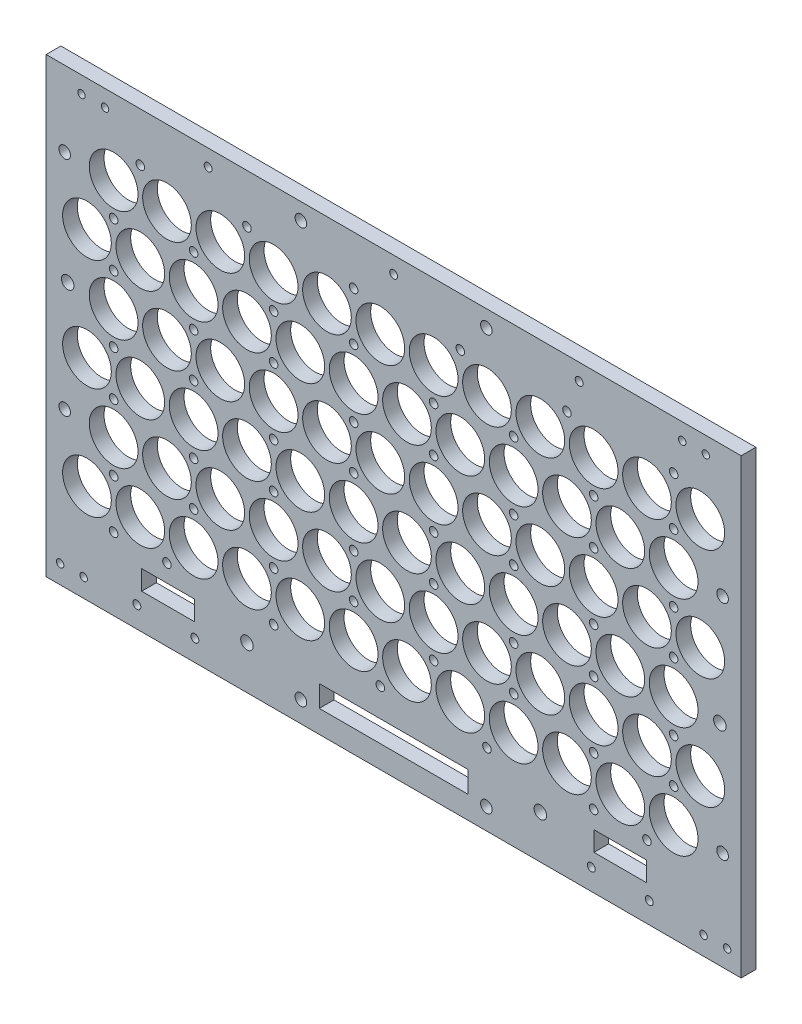
SolidWorks part; units mm, degrees
material "ABS"
ref_plane "X-Y Datum" through (0, 0, 0) normal (0, 0, 1) x (1, 0, 0)
ref_plane "X-Z Datum" through (0, 0, 0) normal (0, 1, 0) x (1, 0, 0)
ref_plane "Y-Z Datum" through (0, 0, 0) normal (1, 0, 0) x (0, 0, -1)
sketch "Sketch1" plane through (0, 0, 0) normal (0, 0, 1) x (1, 0, 0)
  line L1 (-143.025, 70.775) -> (143.025, 70.775)
  line L2 (-143.025, 70.775) -> (-143.025, -70.775)
  line L3 (-143.025, -70.775) -> (143.025, -70.775)
  line L4 (143.025, 70.775) -> (143.025, -70.775)
  line L5 (-143.025, 70.775) -> (143.025, -70.775) construction
  line L6 (-143.025, -70.775) -> (143.025, 70.775) construction
  line L13 (-149.85, -102.6) -> (149.85, -102.6)
  line L14 (-149.85, 91.65) -> (149.85, 91.65)
  line L15 (-149.85, 91.65) -> (-149.85, -102.6)
  line L16 (149.85, 91.65) -> (149.85, -102.6)
  line L17 (149.85, 70.775) -> (149.85, -70.775) construction
  line L18 (-143.025, 91.65) -> (143.025, 91.65) construction
  line L19 (-143.025, -102.6) -> (143.025, -102.6) construction
  line L20 (-149.85, 70.775) -> (-149.85, -70.775) construction
  line L21 (-132.25, -60) -> (-109.25, -60) construction
  circle A0 centre (-132.25, -60) radius 10.775
  circle A1 centre (-109.25, -60) radius 10.775 construction
  circle A2 centre (-120.75, -36) radius 10.775
  point P0 (0, 0)
  point P16 (-120.75, -60)
  dimension "D1" = 21.55
  dimension "D2" = 23
  dimension "D3" = 24
  dimension "D5" = 141.55
  dimension "D6" = 286.05
  dimension "D7" = 31.825
  dimension "D8" = 20.875
  dimension "D9" = 6.825
  dimension "D10" = 6.825
extrude "Boss-Extrude1" add sketch "Sketch1" along normal blind 6.35
sketch "Sketch3" plane through (0, 0, 6.35) normal (0, 0, 1) x (1, 0, 0)
  line L4 (143.025, 70.775) -> (-143.025, 70.775)
  line L5 (143.025, -70.775) -> (143.025, 70.775)
  line L6 (-143.025, -70.775) -> (143.025, -70.775)
  line L7 (-143.025, 70.775) -> (-143.025, -70.775)
  line L8 (143.025, 70.775) -> (-143.025, 70.775)
  line L9 (143.025, -70.775) -> (143.025, 70.775)
  line L10 (-143.025, -70.775) -> (143.025, -70.775)
  line L11 (-143.025, 70.775) -> (-143.025, -70.775)
  circle A0 centre (-132.25, -60) radius 10.4988
  circle A1 centre (-120.75, -36) radius 10.775
  circle A2 centre (-120.75, -36) radius 10.775 construction
  circle A3 centre (-132.25, -60) radius 10.775
  circle A4 centre (-132.25, -60) radius 10.775 construction
  circle A5 centre (-120.75, -36) radius 10.4988
  dimension "D4" = 20.9976
  dimension "D1" = 0
  dimension "D2" = 0
  dimension "D3" = 0
extrude "Cut-Extrude1" cut sketch "Sketch3" against normal through all contours A4 | A0
sketch "Sketch4" plane through (0, 0, 6.35) normal (0, 0, 1) x (1, 0, 0)
  line L12 (143.025, 70.775) -> (-143.025, 70.775)
  line L13 (-143.025, 70.775) -> (-143.025, -70.775)
  line L14 (-143.025, -70.775) -> (143.025, -70.775)
  line L15 (143.025, -70.775) -> (143.025, 70.775)
  line L16 (143.025, 70.775) -> (-143.025, 70.775)
  line L17 (-143.025, 70.775) -> (-143.025, -70.775)
  line L18 (-143.025, -70.775) -> (143.025, -70.775)
  line L19 (143.025, -70.775) -> (143.025, 70.775)
  circle A1 centre (-120.75, -36) radius 10.4988
  circle A3 centre (-120.75, -36) radius 10.4988
  circle A5 centre (-132.25, -60) radius 10.4988
  circle A6 centre (-132.25, -60) radius 10.4988
  dimension "D1" = 0
  dimension "D2" = 0
  dimension "D3" = 0
extrude "Cut-Extrude2" cut sketch "Sketch4" against normal through all contours A3
pattern_linear "LPattern1" count 12 spacing 23 along (1, 0, 0) of "Cut-Extrude1", "Cut-Extrude2"
pattern_linear "LPattern2" count 3 spacing 48 along (0, 1, 0) of "LPattern1", "Cut-Extrude1", "Cut-Extrude2"
sketch "Sketch5" plane through (0, 0, 6.35) normal (0, 0, 1) x (1, 0, 0)
  line L4 (105.3154, -79.3475) -> (90.1846, -79.3475)
  line L5 (90.37, -80.3) -> (90.37, -83.4115)
  line L6 (90.37, -83.4115) -> (105.13, -83.4115)
  line L7 (105.13, -83.4115) -> (105.13, -80.3)
  line L8 (105.3154, -79.3475) -> (90.1846, -79.3475)
  line L9 (90.37, -80.3) -> (90.37, -83.4115)
  line L10 (90.37, -83.4115) -> (105.13, -83.4115)
  line L11 (105.13, -83.4115) -> (105.13, -80.3)
  line L12 (-108.668, -78.95) -> (-108.668, -87.4115)
  line L13 (-108.668, -87.4115) -> (-85.908, -87.4115)
  line L14 (-85.908, -87.4115) -> (-85.908, -78.95)
  line L15 (86.37, -78.95) -> (86.37, -87.4115)
  line L16 (-89.7226, -79.3475) -> (-104.8534, -79.3475)
  line L17 (-104.668, -80.3) -> (-104.668, -83.4115)
  line L18 (-104.668, -83.4115) -> (-89.908, -83.4115)
  line L19 (-89.908, -83.4115) -> (-89.908, -80.3)
  line L20 (-89.7226, -79.3475) -> (-104.8534, -79.3475)
  line L21 (-104.668, -80.3) -> (-104.668, -83.4115)
  line L22 (-104.668, -83.4115) -> (-89.908, -83.4115)
  line L23 (-89.908, -83.4115) -> (-89.908, -80.3)
  line L24 (86.37, -87.4115) -> (109.13, -87.4115)
  line L25 (109.13, -87.4115) -> (109.13, -78.95)
  line L26 (149.85, -78.95) -> (-149.85, -78.95) construction
  line L27 (149.85, -78.95) -> (-149.85, -78.95)
  line L28 (109.13, -87.4115) -> (109.13, -80.3) construction
  line L29 (86.37, -80.3) -> (86.37, -87.4115) construction
  line L30 (-85.908, -87.4115) -> (-85.908, -80.3) construction
  line L31 (-108.668, -80.3) -> (-108.668, -87.4115) construction
  arc A2 (90.37, -80.3) -> (90.1846, -79.3475) centre (87.83, -80.3) ccw
  arc A3 (105.3154, -79.3475) -> (105.13, -80.3) centre (107.67, -80.3) ccw
  arc A4 (90.37, -80.3) -> (90.1846, -79.3475) centre (87.83, -80.3) ccw
  arc A5 (105.3154, -79.3475) -> (105.13, -80.3) centre (107.67, -80.3) ccw
  arc A8 (-104.668, -80.3) -> (-104.8534, -79.3475) centre (-107.208, -80.3) ccw
  arc A9 (-89.7226, -79.3475) -> (-89.908, -80.3) centre (-87.368, -80.3) ccw
  arc A10 (-104.668, -80.3) -> (-104.8534, -79.3475) centre (-107.208, -80.3) ccw
  arc A11 (-89.7226, -79.3475) -> (-89.908, -80.3) centre (-87.368, -80.3) ccw
  dimension "D1" = 0
  dimension "D2" = 0
  dimension "D3" = 4
extrude "Cut-Extrude3" cut sketch "Sketch5" against normal through all contours L25 L27 L15 L24 L8 A5 L11 L10 L9 A4 | A5 L8 A4 L9 L10 L11 | L14 L27 L12 L13 L20 A11 L23 L22 L21 A10 | A11 L20 A10 L21 L22 L23
sketch "Sketch7" plane through (0, 0, 6.35) normal (0, 0, 1) x (1, 0, 0)
  point P0 (0, 85.3)
  point P1 (80, 85.3)
  point P3 (-124.45, 85.3)
  point P5 (-134.61, 85.3)
  point P7 (-133.6575, -94.6)
  point P9 (-143.8175, -94.6)
  point P11 (133.6575, -94.6)
  point P13 (143.8175, -94.6)
  point P17 (124.45, 85.3)
  point P19 (134.61, 85.3)
  point P21 (110.25, -93.5057)
  point P23 (85.25, -93.5057)
  point P28 (-80, 85.3)
hole_wizard "M3 Clearance Hole1" positions "Sketch8" profile "Sketch9" hole size "M3" standard "ANSI Metric" end condition through all
sketch "Sketch8" plane through (0, 0, 6.35) normal (0, 0, 1) x (1, 0, 0)
  point P3 (124.45, 85.3)
  point P6 (134.61, 85.3)
  point P12 (-124.45, 85.3)
  point P15 (-134.61, 85.3)
  point P18 (-143.8175, -94.6)
  point P21 (-133.6575, -94.6)
  point P24 (133.6575, -94.6)
  point P27 (143.8175, -94.6)
sketch "Sketch9" plane through (124.45, 85.3, 6.35) normal (1, 0, 0) x (0, -1, 0)
  line L0 (0, 0) -> (0, 6.35)
  line L1 (0, 6.35) -> (1.6, 6.35)
  line L2 (1.6, 6.35) -> (1.6, 0)
  line L5 (1.6, 0) -> (0, 0)
  line L11 (0, -6.35) -> (0, 107.95) construction
  dimension "Thru Hole Dia." = 3.2
  dimension "Thru Hole Depth" = 6.35
hole_wizard "M3 Clearance Hole2" positions "Sketch20" profile "Sketch13" hole size "M3" standard "ANSI Metric" end condition through all
sketch "Sketch20" plane through (0, 0, 6.35) normal (0, 0, 1) x (1, 0, 0)
  point P0 (110.25, -93.5057)
  point P3 (85.25, -93.5057)
  point P6 (-80, 85.3)
  point P9 (0, 85.3)
  point P12 (80, 85.3)
sketch "Sketch13" plane through (110.25, -93.5057, 6.35) normal (1, 0, 0) x (0, -1, 0)
  line L0 (0, 0) -> (0, 6.35)
  line L1 (0, 6.35) -> (1.7, 6.35)
  line L2 (1.7, 6.35) -> (1.7, 0)
  line L5 (1.7, 0) -> (0, 0)
  line L11 (0, -6.35) -> (0, 107.95) construction
  dimension "Thru Hole Dia." = 3.4
  dimension "Thru Hole Depth" = 6.35
sketch "Sketch14" plane through (0, 0, 6.35) normal (0, 0, 1) x (1, 0, 0)
  line L0 (131.525, -12) -> (149.85, -12) construction
  line L1 (149.85, 91.65) -> (149.85, -102.6) construction
  line L2 (-131.2488, 12) -> (-149.85, 12) construction
  line L3 (-149.85, 91.65) -> (-149.85, -102.6) construction
  line L4 (149.85, -78.95) -> (-149.85, -78.95) construction
  line L5 (149.85, -78.95) -> (-149.85, -78.95) construction
  line L6 (149.85, -83.95) -> (-149.85, -83.95) construction
  line L7 (68.55, -70.9014) -> (57.95, -70.9014) construction
  line L8 (68.55, -67.0427) -> (68.55, -74.76) construction
  line L9 (57.95, -67.0427) -> (57.95, -74.76) construction
  line L10 (63.25, -70.9014) -> (63.25, -83.95) construction
  line L18 (0, -3.4925) -> (0, 3.4925) construction
  circle A1 centre (-120.75, 12) radius 10.4988 construction
  circle A2 centre (140.6875, -12) radius 2.7
  circle A3 centre (-140.5494, 12) radius 2.7
  circle A4 centre (63.25, -83.95) radius 2.7
  circle A6 centre (-63.25, -83.95) radius 2.7
  circle A8 centre (0, -83.95) radius 2.7
  dimension "D1" = 5.4
  dimension "D3" = 5.4
  dimension "D2" = 5
extrude "Cut-Extrude4" cut sketch "Sketch14" against normal through all contours A6 | A4 | A3 | A2
sketch "Sketch15" plane through (0, 0, 6.35) normal (0, 0, 1) x (1, 0, 0)
  line L0 (-6.35, 85.3) -> (86.35, 85.3) construction
  line L1 (-6.35, 90.65) -> (-6.35, 79.95) construction
  line L2 (86.35, 79.95) -> (86.35, 90.65) construction
  line L3 (-86.35, 85.3) -> (6.35, 85.3) construction
  line L4 (-86.35, 90.65) -> (-86.35, 79.95) construction
  line L5 (6.35, 79.95) -> (6.35, 90.65) construction
  line L6 (131.525, 36) -> (149.85, 36) construction
  line L7 (149.85, 94.825) -> (149.85, -105.775) construction
  line L8 (131.525, -60) -> (149.85, -60) construction
  line L9 (-131.2488, -36) -> (-149.85, -36) construction
  line L10 (-149.85, -105.775) -> (-149.85, 94.825) construction
  line L11 (-131.2488, 60) -> (-149.85, 60) construction
  line L12 (-40, 85.3) -> (-40, -102.6) construction
  line L13 (-149.85, -102.6) -> (149.85, -102.6) construction
  line L14 (40, 85.3) -> (40, -102.6) construction
  line L16 (85.25, -93.5057) -> (-85.25, -93.5057) construction
  circle A0 centre (-40, 85.3) radius 2.5
  circle A1 centre (40, 85.3) radius 2.5
  circle A4 centre (141.85, 36) radius 2.5
  circle A5 centre (141.85, -60) radius 2.5
  circle A6 centre (-120.75, -36) radius 10.4988 construction
  circle A7 centre (-120.75, 60) radius 10.4988 construction
  circle A8 centre (-141.85, -36) radius 2.5
  circle A9 centre (-141.85, 60) radius 2.5
  circle A10 centre (-40, -93.5057) radius 2.5
  circle A11 centre (40, -93.5057) radius 2.5
  dimension "D1" = 5
  dimension "D2" = 8
  dimension "D3" = 8
  dimension "D4" = 8
  dimension "D5" = 8
extrude "Cut-Extrude5" cut sketch "Sketch15" against normal through all
sketch "Sketch18" plane through (0, 0, 6.35) normal (0, 0, 1) x (1, 0, 0)
  circle A0 centre (-120.75, -71.41) radius 1.5875 construction
  circle A1 centre (-97.75, -71.41) radius 1.5875 construction
  circle A2 centre (-51.75, -71.41) radius 1.5875 construction
  circle A3 centre (-5.75, -71.41) radius 1.5875 construction
  circle A4 centre (40.25, -71.41) radius 1.5875 construction
  circle A5 centre (-109.25, 71.41) radius 1.5875 construction
  circle A6 centre (-63.25, 71.41) radius 1.5875 construction
  circle A7 centre (-17.25, 71.41) radius 1.5875 construction
  circle A8 centre (28.75, 71.41) radius 1.5875 construction
  circle A9 centre (74.75, 71.41) radius 1.5875 construction
  circle A10 centre (120.75, 71.41) radius 1.5875 construction
  circle A11 centre (86.25, -71.41) radius 1.5875 construction
  circle A12 centre (109.25, -71.41) radius 1.5875 construction
  circle A13 centre (-120.75, -71.41) radius 1.5875 construction
  circle A14 centre (-97.75, -71.41) radius 1.5875 construction
  circle A15 centre (-51.75, -71.41) radius 1.5875 construction
  circle A16 centre (-5.75, -71.41) radius 1.5875 construction
  circle A17 centre (40.25, -71.41) radius 1.5875 construction
  circle A18 centre (-109.25, 71.41) radius 1.5875 construction
  circle A19 centre (-63.25, 71.41) radius 1.5875 construction
  circle A20 centre (-17.25, 71.41) radius 1.5875 construction
  circle A21 centre (28.75, 71.41) radius 1.5875 construction
  circle A22 centre (74.75, 71.41) radius 1.5875 construction
  circle A23 centre (120.75, 71.41) radius 1.5875 construction
  circle A24 centre (86.25, -71.41) radius 1.5875 construction
  circle A25 centre (109.25, -71.41) radius 1.5875 construction
  circle A26 centre (109.25, -71.41) radius 1.8415
  circle A27 centre (86.25, -71.41) radius 1.8415
  circle A28 centre (120.75, 71.41) radius 1.8415
  circle A29 centre (74.75, 71.41) radius 1.8415
  circle A30 centre (28.75, 71.41) radius 1.8415
  circle A31 centre (-17.25, 71.41) radius 1.8415
  circle A32 centre (-63.25, 71.41) radius 1.8415
  circle A33 centre (-109.25, 71.41) radius 1.8415
  circle A34 centre (40.25, -71.41) radius 1.8415
  circle A35 centre (-5.75, -71.41) radius 1.8415
  circle A36 centre (-51.75, -71.41) radius 1.8415
  circle A37 centre (-97.75, -71.41) radius 1.8415
  circle A38 centre (-120.75, -71.41) radius 1.8415
  dimension "D1" = 3.683
extrude "Cut-Extrude7" cut sketch "Sketch18" against normal through all
sketch "Sketch19" plane through (0, 91.65, 0) normal (0, 1, 0) x (1, 0, 0)
  line L4 (149.85, 0) -> (-149.85, 0)
  line L5 (-149.85, 0) -> (-149.85, -6.35)
  line L6 (-149.85, -6.35) -> (149.85, -6.35)
  line L7 (149.85, -6.35) -> (149.85, 0)
  line L8 (149.85, 0) -> (-149.85, 0)
  line L9 (-149.85, 0) -> (-149.85, -6.35)
  line L10 (-149.85, -6.35) -> (149.85, -6.35)
  line L11 (149.85, -6.35) -> (149.85, 0)
  dimension "D1" = 0
extrude "Boss-Extrude2" add sketch "Sketch19" along normal blind 0.7937
sketch "Sketch22" plane through (0, 0, 6.35) normal (0, 0, 1) x (1, 0, 0)
  line L0 (132.25, -36) -> (120.75, -60) construction
  line L1 (120.75, -60) -> (109.25, -36) construction
  line L2 (109.25, -36) -> (132.25, -36) construction
  line L3 (120.75, -36) -> (120.75, -60) construction
  line L4 (127.7133, -45.468) -> (113.7867, -45.468) construction
  line L5 (109.25, -36) -> (97.75, -60) construction
  line L6 (97.75, -60) -> (86.25, -36) construction
  line L7 (86.25, -36) -> (109.25, -36) construction
  line L8 (97.75, -60) -> (97.75, -36) construction
  line L9 (113.7867, -45.468) -> (90.7867, -45.468) construction
  line L10 (86.25, -36) -> (74.75, -60) construction
  line L11 (74.75, -60) -> (63.25, -36) construction
  line L12 (63.25, -36) -> (86.25, -36) construction
  line L13 (74.75, -36) -> (74.75, -60) construction
  line L14 (90.7867, -45.468) -> (67.7867, -45.468) construction
  line L15 (74.75, -60) -> (97.75, -60) construction
  line L16 (86.25, -36) -> (86.25, -60) construction
  line L17 (79.4061, -50.2829) -> (93.0939, -50.2829) construction
  circle A0 centre (132.25, -36) radius 10.4988 construction
  circle A1 centre (109.25, -36) radius 10.4988 construction
  circle A2 centre (120.75, -45.468) radius 1.8415
  circle A3 centre (86.25, -36) radius 10.4988 construction
  circle A8 centre (86.25, -50.2829) radius 1.8415
  dimension "D1" = 3.683
extrude "Cut-Extrude8" cut sketch "Sketch22" against normal through all
pattern_linear "LPattern3" count 3 spacing 48 along (0, 1, 0) of "Cut-Extrude8"
sketch "Sketch23" plane through (0, 0, 6.35) normal (0, 0, 1) x (1, 0, 0)
  line L0 (132.25, -36) -> (120.75, -12) construction
  line L1 (120.75, -12) -> (109.25, -36) construction
  line L2 (109.25, -36) -> (132.25, -36) construction
  line L3 (120.75, -36) -> (120.75, -12) construction
  line L4 (109.25, -36) -> (97.75, -12) construction
  line L5 (97.75, -12) -> (86.25, -36) construction
  line L6 (86.25, -36) -> (109.25, -36) construction
  line L7 (97.75, -36) -> (97.75, -12) construction
  line L8 (127.7133, -26.532) -> (90.7867, -26.532) construction
  line L9 (86.25, -36) -> (63.25, -36) construction
  line L10 (63.25, -36) -> (74.75, -12) construction
  line L11 (74.75, -12) -> (86.25, -36) construction
  line L12 (74.75, -36) -> (74.75, -12) construction
  line L13 (90.7867, -26.532) -> (67.7867, -26.532) construction
  line L14 (74.75, -12) -> (97.75, -12)
  line L15 (86.25, -12) -> (86.25, -36) construction
  line L16 (79.4061, -21.7171) -> (93.0939, -21.7171) construction
  circle A0 centre (132.25, -36) radius 10.4988 construction
  circle A1 centre (86.25, -36) radius 10.4988 construction
  circle A2 centre (120.75, -26.532) radius 1.8415
  circle A7 centre (86.25, -21.7171) radius 1.8415
  dimension "D1" = 3.683
extrude "Cut-Extrude9" cut sketch "Sketch23" against normal through all contours A7 | A2
pattern_linear "LPattern4" count 2 spacing 48 along (0, 1, 0) of "Cut-Extrude9"
pattern_linear "LPattern5" count 4 spacing 69 along (-1, 0, 0) of "Cut-Extrude8", "LPattern3", "Cut-Extrude9", "LPattern4"
sketch "Sketch25" plane through (0, 0, 6.35) normal (0, 0, 1) x (1, 0, 0)
  line L0 (-85.712, -93.486) -> (-110.712, -93.486)
  line L1 (-149.85, -102.6) -> (149.85, -102.6) construction
  line L3 (-149.85, 92.4437) -> (-149.85, -102.6) construction
  circle A0 centre (-110.712, -93.486) radius 1.5
  circle A1 centre (-85.712, -93.486) radius 1.5
  point P7 (-98.212, -93.486)
  dimension "D1" = 3
  dimension "D2" = 25
  dimension "D3" = 9.114
  dimension "D4" = 39.138
hole_wizard "M3 Clearance Hole3" positions "Sketch30" profile "Sketch29" hole size "M3" standard "ANSI Metric" end condition through all
sketch "Sketch30" plane through (0, 0, 6.35) normal (0, 0, 1) x (1, 0, 0)
  point P0 (-85.712, -93.486)
  point P3 (-110.712, -93.486)
sketch "Sketch29" plane through (-85.712, -93.486, 6.35) normal (1, 0, 0) x (0, -1, 0)
  line L0 (0, 0) -> (0, 6.35)
  line L1 (0, 6.35) -> (1.7, 6.35)
  line L2 (1.7, 6.35) -> (1.7, 0)
  line L5 (1.7, 0) -> (0, 0)
  line L11 (0, -6.35) -> (0, 107.95) construction
  dimension "Thru Hole Dia." = 3.4
  dimension "Thru Hole Depth" = 6.35
sketch "Sketch31" plane through (0, 0, 6.35) normal (0, 0, 1) x (1, 0, 0)
  line L0 (0, -102.6) -> (0, 92.4437) construction
  line L1 (-149.85, -102.6) -> (149.85, -102.6) construction
  line L2 (149.85, 92.4437) -> (-149.85, 92.4437) construction
  line L3 (-32.0675, -92.8738) -> (32.0675, -92.8738)
  line L4 (-30.48, -91.2863) -> (30.48, -91.2863) construction
  line L5 (-30.48, -91.2863) -> (-30.48, -85.1863) construction
  line L6 (-30.48, -85.1863) -> (30.48, -85.1863) construction
  line L7 (30.48, -91.2863) -> (30.48, -85.1863) construction
  line L8 (-30.48, -91.2863) -> (30.48, -85.1863) construction
  line L9 (-30.48, -85.1863) -> (30.48, -91.2863) construction
  line L10 (32.0675, -92.8738) -> (32.0675, -83.5988)
  line L11 (-32.0675, -83.5988) -> (32.0675, -83.5988)
  line L12 (-32.0675, -92.8738) -> (-32.0675, -83.5988)
  point P6 (0, -88.2363)
  dimension "D1" = 11.3137
  dimension "D2" = 6.1
  dimension "D3" = 60.96
  dimension "D4" = 1.5875
extrude "Cut-Extrude10" cut sketch "Sketch31" against normal through all
